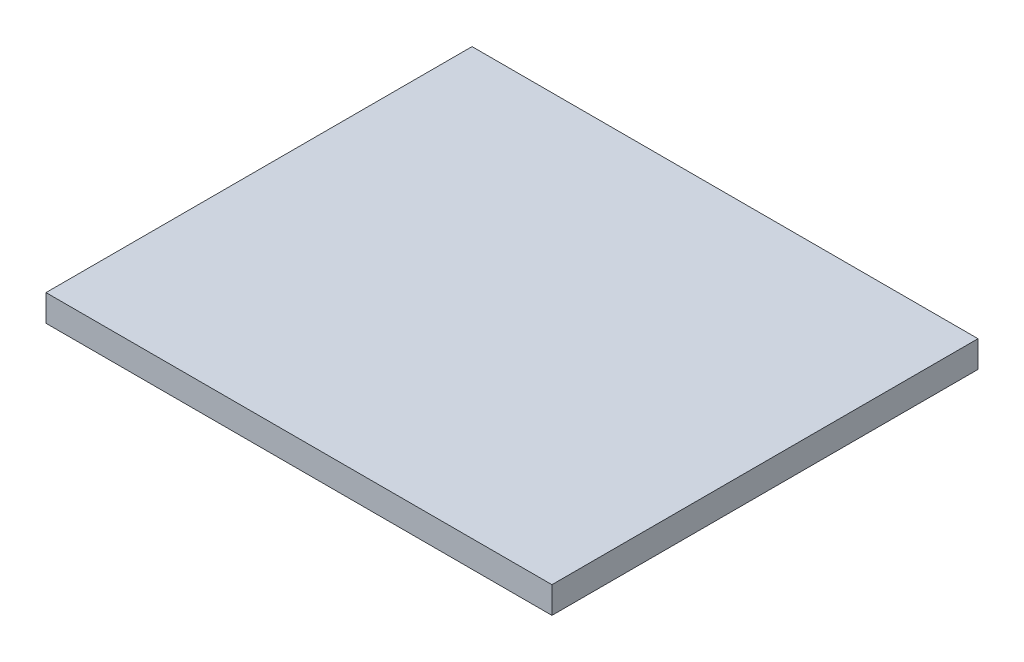
SolidWorks part; units mm, degrees
ref_plane "Front Plane" through (0, 0, 0) normal (0, 0, 1) x (1, 0, 0)
ref_plane "Top Plane" through (0, 0, 0) normal (0, 1, 0) x (1, 0, 0)
ref_plane "Right Plane" through (0, 0, 0) normal (1, 0, 0) x (0, 0, -1)
sketch "Sketch1" plane through (0, 0, 0) normal (0, 1, 0) x (1, 0, 0)
  line L1 (-9.5, -8) -> (9.5, -8)
  line L2 (-9.5, -8) -> (-9.5, 8)
  line L3 (-9.5, 8) -> (9.5, 8)
  line L4 (9.5, -8) -> (9.5, 8)
  line L5 (-9.5, -8) -> (9.5, 8) construction
  line L6 (-9.5, 8) -> (9.5, -8) construction
  point P0 (0, 0)
  dimension "D1" = 16
  dimension "D2" = 19
extrude "Boss-Extrude1" add sketch "Sketch1" along normal blind 1
